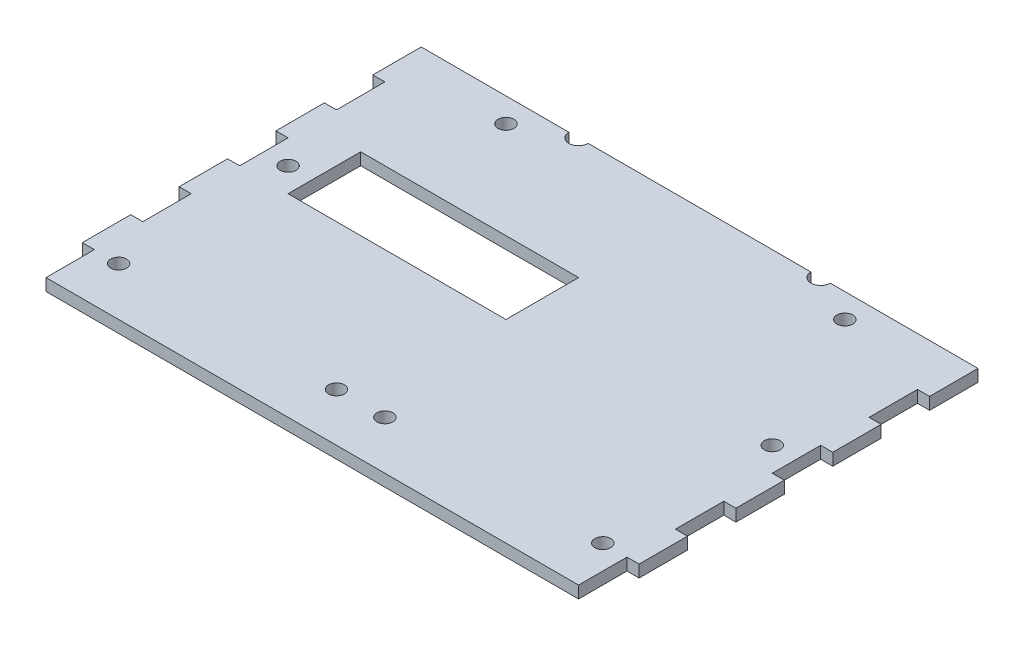
SolidWorks part; units mm, degrees
ref_plane "Front Plane" through (0, 0, 0) normal (0, 0, 1) x (1, 0, 0)
ref_plane "Top Plane" through (0, 0, 0) normal (0, 1, 0) x (1, 0, 0)
ref_plane "Right Plane" through (0, 0, 0) normal (1, 0, 0) x (0, 0, -1)
sketch "Sketch2" plane through (0, 0, 0) normal (0, 1, 0) x (1, 0, 0)
  line L0 (3.175, 0) -> (3.175, 12.7)
  line L1 (3.175, 12.7) -> (0, 12.7)
  line L2 (0, 50.8) -> (0, 38.1)
  line L3 (0, 25.4) -> (3.175, 25.4)
  line L4 (3.175, 38.1) -> (0, 38.1)
  line L5 (0, 76.2) -> (0, 63.5)
  line L6 (0, 50.8) -> (3.175, 50.8)
  line L7 (3.175, 63.5) -> (0, 63.5)
  line L8 (146.05, 101.6) -> (146.05, 88.9)
  line L9 (0, 76.2) -> (3.175, 76.2)
  line L10 (3.175, 25.4) -> (3.175, 38.1)
  line L11 (3.175, 88.9) -> (0, 88.9)
  line L12 (146.05, 25.4) -> (146.05, 12.7)
  line L13 (0, 101.6) -> (3.175, 101.6)
  line L14 (3.175, 50.8) -> (3.175, 63.5)
  line L15 (3.175, 88.9) -> (28.575, 88.9) construction
  line L16 (28.575, 88.9) -> (28.575, 95.25) construction
  line L17 (117.475, 88.9) -> (117.475, 95.25) construction
  line L18 (3.175, 76.2) -> (3.175, 88.9)
  line L19 (9.525, 0) -> (9.525, 12.7) construction
  line L20 (136.525, 0) -> (136.525, 12.7) construction
  line L21 (3.175, 101.6) -> (38.735, 101.6)
  line L22 (142.875, 88.9) -> (117.475, 88.9) construction
  line L23 (73.025, 101.6) -> (73.025, 0) construction
  line L24 (142.875, 57.15) -> (136.525, 57.15) construction
  line L25 (0, 101.6) -> (0, 88.9)
  line L26 (0, 25.4) -> (0, 12.7)
  line L27 (146.05, 50.8) -> (146.05, 38.1)
  line L28 (146.05, 76.2) -> (146.05, 63.5)
  line L29 (43.815, 101.6) -> (102.235, 101.6)
  line L30 (142.875, 76.2) -> (142.875, 88.9)
  line L31 (107.315, 101.6) -> (142.875, 101.6)
  line L32 (3.175, 50.8) -> (142.875, 50.8) construction
  line L33 (73.025, 0) -> (73.025, 12.7) construction
  line L34 (142.875, 50.8) -> (142.875, 63.5)
  line L35 (146.05, 101.6) -> (142.875, 101.6)
  line L36 (15.875, 69.85) -> (15.875, 50.8)
  line L37 (142.875, 88.9) -> (146.05, 88.9)
  line L38 (142.875, 25.4) -> (142.875, 38.1)
  line L39 (146.05, 76.2) -> (142.875, 76.2)
  line L40 (15.875, 50.8) -> (73.025, 50.8)
  line L41 (142.875, 63.5) -> (146.05, 63.5)
  line L42 (146.05, 50.8) -> (142.875, 50.8)
  line L43 (73.025, 50.8) -> (73.025, 69.85)
  line L44 (142.875, 38.1) -> (146.05, 38.1)
  line L45 (146.05, 25.4) -> (142.875, 25.4)
  line L46 (73.025, 69.85) -> (15.875, 69.85)
  line L47 (142.875, 12.7) -> (146.05, 12.7)
  line L48 (142.875, 0) -> (142.875, 12.7)
  line L49 (142.875, 0) -> (3.175, 0)
  line L50 (73.025, 12.7) -> (66.675, 12.7) construction
  line L52 (3.175, 57.15) -> (9.525, 57.15) construction
  circle A0 centre (136.525, 57.15) radius 2.0828
  circle A1 centre (9.525, 12.7) radius 2.0828
  circle A2 centre (9.525, 57.15) radius 2.0828
  circle A3 centre (136.525, 12.7) radius 2.0828
  circle A4 centre (28.575, 95.25) radius 2.0828
  circle A5 centre (117.475, 95.25) radius 2.0828
  arc A6 (38.735, 101.6) -> (43.815, 101.6) centre (41.275, 101.6) ccw
  arc A7 (107.315, 101.6) -> (102.235, 101.6) centre (104.775, 101.6) cw
  circle A8 centre (66.675, 12.7) radius 2.0828
  circle A9 centre (79.375, 12.7) radius 2.0828
  point P66 (69.85, 12.7)
  point P67 (76.2, 12.7)
  dimension "D1" = 12.7
  dimension "D3" = 6.35
  dimension "D2" = 25.4
  dimension "D5" = 38.1
  dimension "D4" = 12.7
  dimension "D7" = 19.05
extrude "Boss-Extrude1" add sketch "Sketch2" along normal blind 3.175
